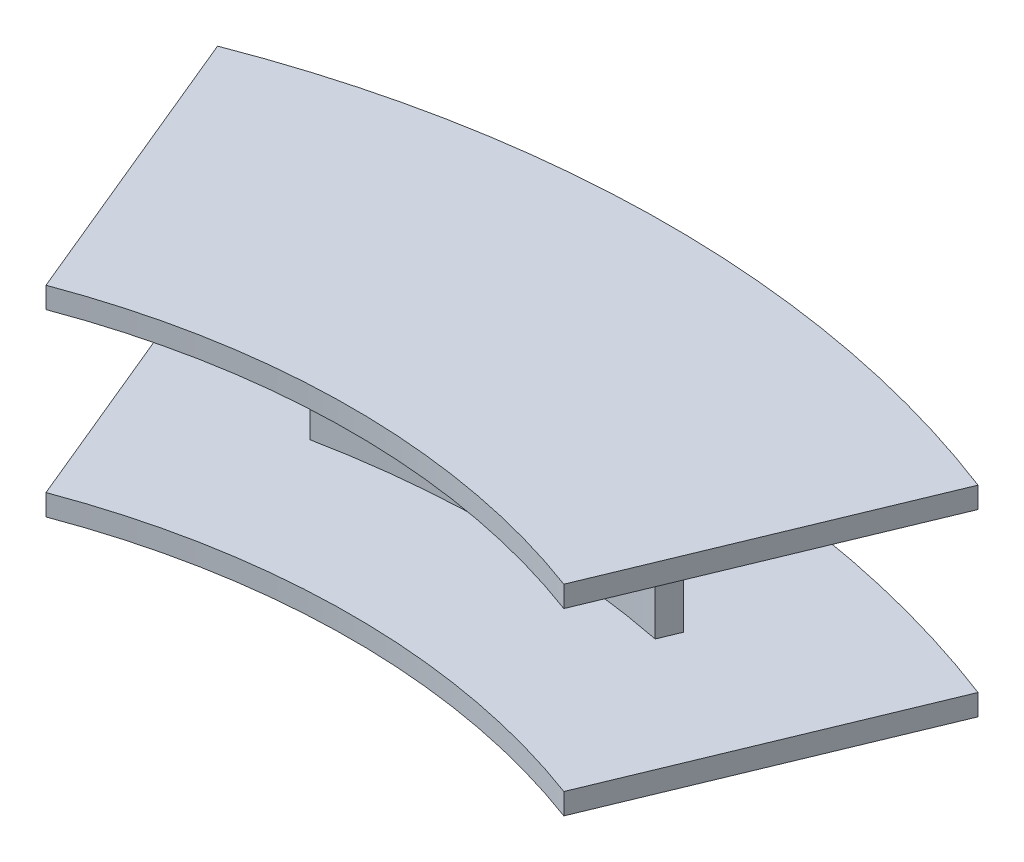
SolidWorks part; units mm, degrees
material "ABS"
ref_plane "Front Plane" through (0, 0, 0) normal (0, 0, 1) x (1, 0, 0)
ref_plane "Top Plane" through (0, 0, 0) normal (0, 1, 0) x (1, 0, 0)
ref_plane "Right Plane" through (0, 0, 0) normal (1, 0, 0) x (0, 0, -1)
sketch "Sketch1" plane through (0, 0, 0) normal (0, 1, 0) x (1, 0, 0)
  line L0 (-180.222, 53.0026) -> (-122.795, -85.6384)
  line L1 (122.351, -85.6384) -> (179.778, 53.0026)
  arc A0 (-122.795, -85.6384) -> (122.351, -85.6384) centre (-0.222, -413.4735) cw
  arc A1 (179.778, 53.0026) -> (-180.222, 53.0026) centre (-0.222, -413.4735) ccw
extrude "Boss-Extrude1" add sketch "Sketch1" along normal mid plane 10
sketch "Sketch2" plane through (0, 5, 0) normal (0, 1, 0) x (1, 0, 0)
  line L0 (-85.784, 7.9279) -> (-81.8835, -1.4888)
  line L1 (81.4394, -1.4888) -> (85.34, 7.9279)
  line L2 (-180.222, 53.0026) -> (-122.795, -85.6384)
  line L3 (122.351, -85.6384) -> (179.778, 53.0026)
  line L4 (-180.222, 53.0026) -> (-122.795, -85.6384) construction
  line L5 (122.351, -85.6384) -> (179.778, 53.0026) construction
  arc A0 (85.34, 7.9279) -> (-85.784, 7.9279) centre (-0.222, -413.4735) ccw
  arc A1 (81.4394, -1.4888) -> (-81.8835, -1.4888) centre (-0.222, -413.4735) ccw
  arc A2 (179.778, 53.0026) -> (-180.222, 53.0026) centre (-0.222, -413.4735) ccw
  arc A3 (122.351, -85.6384) -> (-122.795, -85.6384) centre (-0.222, -413.4735) ccw
  arc A4 (179.778, 53.0026) -> (-180.222, 53.0026) centre (-0.222, -413.4735) ccw construction
  arc A5 (122.351, -85.6384) -> (-122.795, -85.6384) centre (-0.222, -413.4735) ccw construction
  dimension "D1" = 0
  dimension "D2" = 70
extrude "Boss-Extrude2" add sketch "Sketch2" along normal blind 75
ref_plane "Plane1" through (0, 42.5, 0) normal (0, 1, 0) x (1, 0, 0)
mirror "Mirror1" about plane through (0, 42.5, 0) normal (0, 1, 0) of "Boss-Extrude1"
